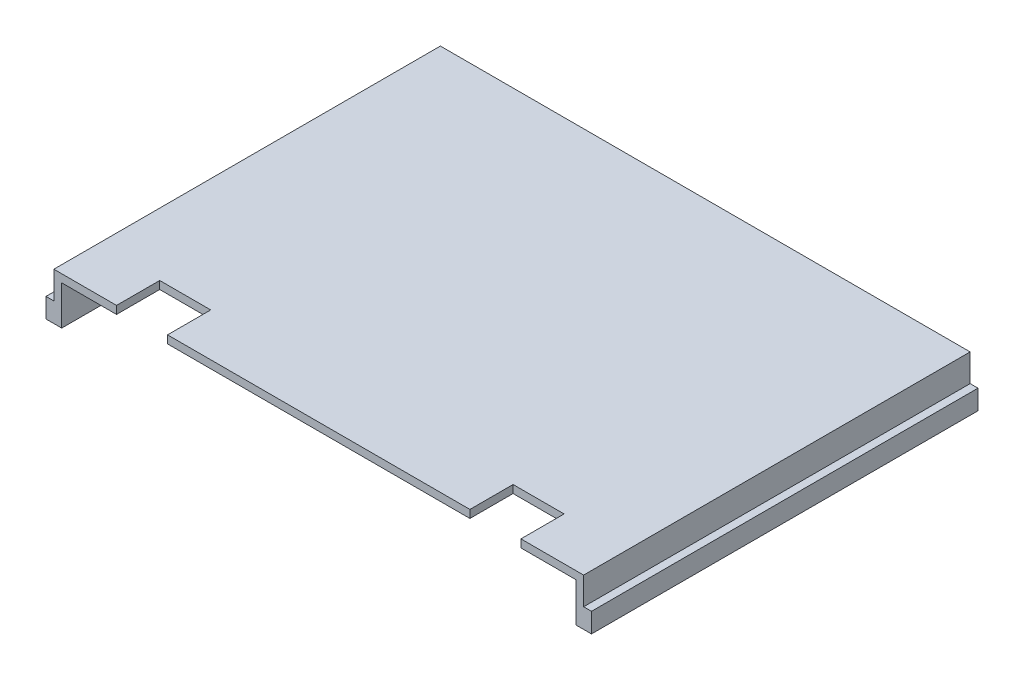
SolidWorks part; units mm, degrees
ref_plane "Alzado" through (0, 0, 0) normal (0, 0, 1) x (1, 0, 0)
ref_plane "Planta" through (0, 0, 0) normal (0, 1, 0) x (1, 0, 0)
ref_plane "Vista lateral" through (0, 0, 0) normal (1, 0, 0) x (0, 0, -1)
sketch "Croquis1" plane through (0, 0, 0) normal (0, 0, 1) x (1, 0, 0)
  line L1 (219.3659, 10.0122) -> (-50.6341, 10.0122)
  line L2 (-50.6341, 10.0122) -> (-50.6341, -3.9878)
  line L6 (-46.6341, -3.9878) -> (-46.6341, 6.0122)
  line L7 (-46.6341, 6.0122) -> (215.3659, 6.0122)
  line L8 (219.1358, -13.9878) -> (215.3659, -13.9878)
  line L9 (219.3659, 10.0122) -> (219.3659, -3.9878)
  line L10 (215.3659, -3.9878) -> (215.3659, 6.0122)
  line L13 (-46.6341, 1.0122) -> (-50.6341, 1.0122) construction
  line L14 (-50.6341, 1.0122) -> (-46.6341, 1.0122) construction
  line L15 (-20.5689, 10.0122) -> (-20.5689, 6.0122) construction
  line L16 (215.3659, 1.0122) -> (219.3659, 1.0122) construction
  line L17 (-50.6341, -3.9878) -> (-54.6341, -3.9878)
  line L18 (-54.6341, -3.9878) -> (-54.6341, -13.9878)
  line L19 (-54.6341, -13.9878) -> (-49.3449, -13.9878)
  line L20 (-46.6341, -3.9878) -> (-46.6341, -13.9878)
  line L21 (-46.6341, -13.9878) -> (-49.3449, -13.9878)
  line L22 (219.3659, -3.9878) -> (223.3659, -3.9878)
  line L23 (223.3659, -3.9878) -> (223.3659, -13.9878)
  line L24 (223.3659, -13.9878) -> (219.1358, -13.9878)
  line L25 (215.3659, -3.9878) -> (215.3659, -13.9878)
  dimension "D1" = 4
  dimension "D2" = 4
  dimension "D3" = 270
extrude "Saliente-Extruir1" add sketch "Croquis1" along normal blind 197
sketch "Croquis3" plane through (0, 10.0122, 0) normal (0, 1, 0) x (1, 0, 0)
  line L0 (219.3659, -197) -> (-50.6341, -197) construction
  line L1 (-50.6341, -197) -> (-50.6341, 0) construction
  line L2 (-18.6841, -197) -> (-18.6841, -175) construction
  line L3 (-18.6841, -175) -> (7.3159, -175) construction
  line L4 (7.3159, -175) -> (7.3159, -197) construction
  line L5 (7.3159, -197) -> (-18.6841, -197) construction
  line L6 (84.3659, 0) -> (84.3659, -197) construction
  line L7 (219.3659, 0) -> (-50.6341, 0) construction
  line L8 (161.4159, -175) -> (161.4159, -197) construction
  line L9 (161.4159, -197) -> (187.4159, -197) construction
  line L10 (187.4159, -197) -> (187.4159, -175) construction
  line L11 (187.4159, -175) -> (161.4159, -175) construction
  line L13 (-18.6841, -197) -> (7.3159, -197)
  line L14 (-18.6841, -197) -> (-18.6841, -175)
  line L15 (-18.6841, -175) -> (7.3159, -175)
  line L16 (7.3159, -197) -> (7.3159, -175)
  line L17 (161.4159, -197) -> (187.4159, -197)
  line L18 (161.4159, -197) -> (161.4159, -175)
  line L19 (161.4159, -175) -> (187.4159, -175)
  line L20 (187.4159, -197) -> (187.4159, -175)
  dimension "D1" = 31.95
  dimension "D2" = 22
  dimension "D3" = 26
extrude "Cortar-Extruir1" cut sketch "Croquis3" against normal through all
